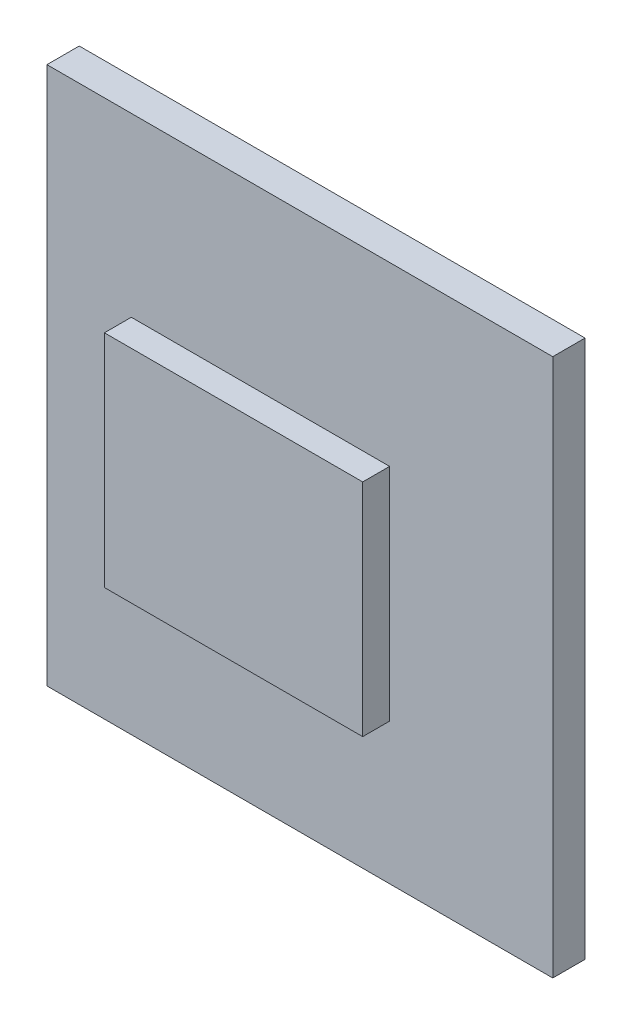
SolidWorks part; units mm, degrees
material "PVC Rigid"
ref_plane "Front Plane" through (0, 0, 0) normal (0, 0, 1) x (1, 0, 0)
ref_plane "Top Plane" through (0, 0, 0) normal (0, 1, 0) x (1, 0, 0)
ref_plane "Right Plane" through (0, 0, 0) normal (1, 0, 0) x (0, 0, -1)
sketch "Sketch1" plane through (0, 0, 0) normal (0, 0, 1) x (1, 0, 0)
  line L1 (0, 0) -> (9.4, 0)
  line L2 (0, 0) -> (0, 10)
  line L3 (0, 10) -> (9.4, 10)
  line L4 (9.4, 0) -> (9.4, 10)
  dimension "D1" = 9.4
  dimension "D2" = 10
extrude "Boss-Extrude1" add sketch "Sketch1" along normal blind 0.6
sketch "Sketch2" plane through (0, 0, 0.6) normal (0, 0, 1) x (1, 0, 0)
  line L1 (1.568, 6.7182) -> (6.368, 6.7182)
  line L2 (1.568, 6.7182) -> (1.568, 2.6182)
  line L3 (1.568, 2.6182) -> (6.368, 2.6182)
  line L4 (6.368, 6.7182) -> (6.368, 2.6182)
  dimension "D1" = 4.8
  dimension "D2" = 4.1
extrude "Boss-Extrude2" add sketch "Sketch2" along normal blind 0.5
